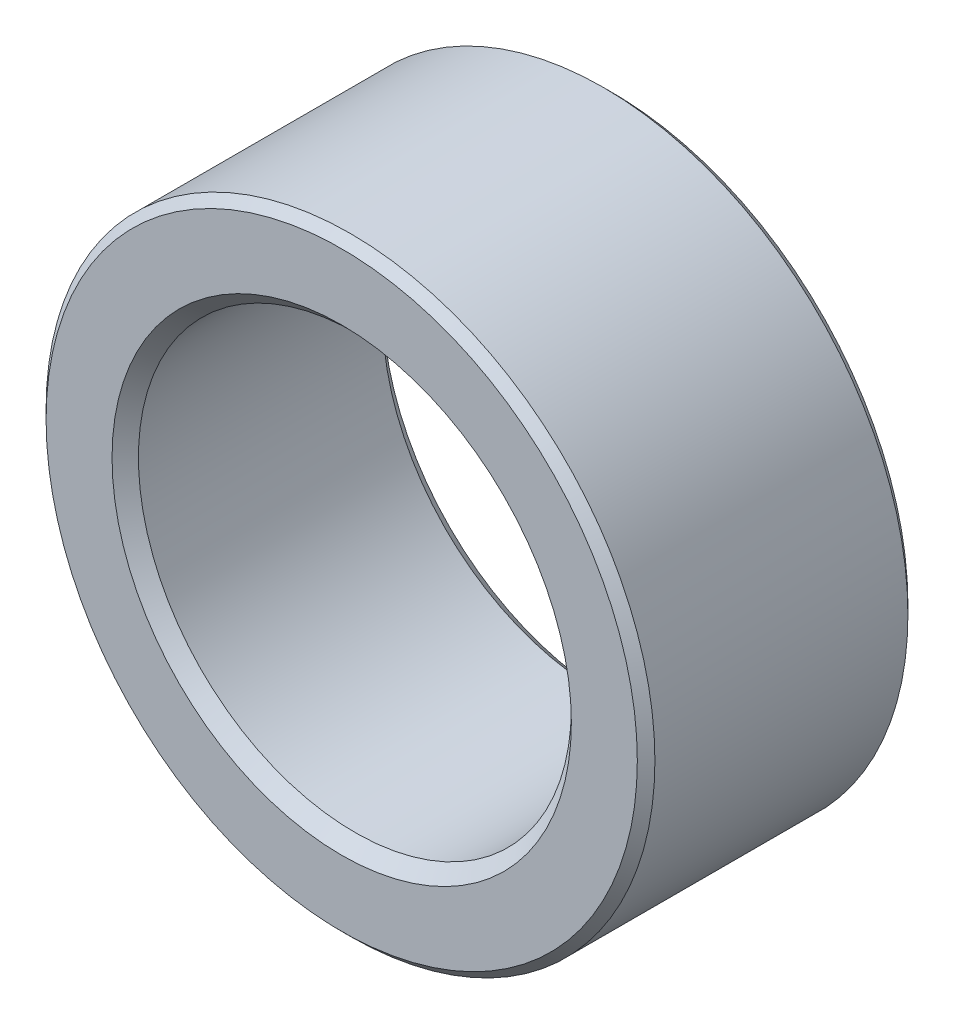
SolidWorks part; units mm, degrees
ref_plane "Front Plane" through (0, 0, 0) normal (0, 0, 1) x (1, 0, 0)
ref_plane "Top Plane" through (0, 0, 0) normal (0, 1, 0) x (1, 0, 0)
ref_plane "Right Plane" through (0, 0, 0) normal (1, 0, 0) x (0, 0, -1)
sketch "Sketch1" plane through (0, 0, 0) normal (0, 0, 1) x (1, 0, 0)
  circle A0 centre (0, 0) radius 2.25 construction
  circle A1 centre (0, 0) radius 1.6 construction
  point P4 (0, 2.25)
  dimension "ID" = 3.2
  dimension "OD" = 4.5
sketch "Sketch2" plane through (0, 0, 0) normal (1, 0, 0) x (0, 0, -1)
  line L0 (-1, 2.25) -> (1, 2.25) construction
  dimension "Length" = 2
sketch "Sketch3" plane through (0, 0, 0) normal (0, 0, 1) x (1, 0, 0)
  circle A0 centre (0, 0) radius 1.6 construction
  circle A1 centre (0, 0) radius 2.25 construction
  circle A2 centre (0, 0) radius 1.6
  circle A3 centre (0, 0) radius 2.25
extrude "Boss-Extrude1" add sketch "Sketch3" against normal up to vertex (1 mm away) and the other way up to vertex (1 mm away) up to point (0, 2.25, -1) other way up to point (0, 2.25, 1)
chamfer "Chamfer1" distance 0.065 angle 45 2 edges at (2.25, 0, 1) (2.25, 0, -1)
chamfer "Chamfer2" distance 0.0975 angle 45 2 edges at (1.6, 0, 1) (1.6, 0, -1)
equation "\"D1@Chamfer1\"=(\"OD@Sketch1\"-\"ID@Sketch1\")*0.05"
equation "\"D1@Chamfer2\"=(\"OD@Sketch1\"-\"ID@Sketch1\")*0.075"
